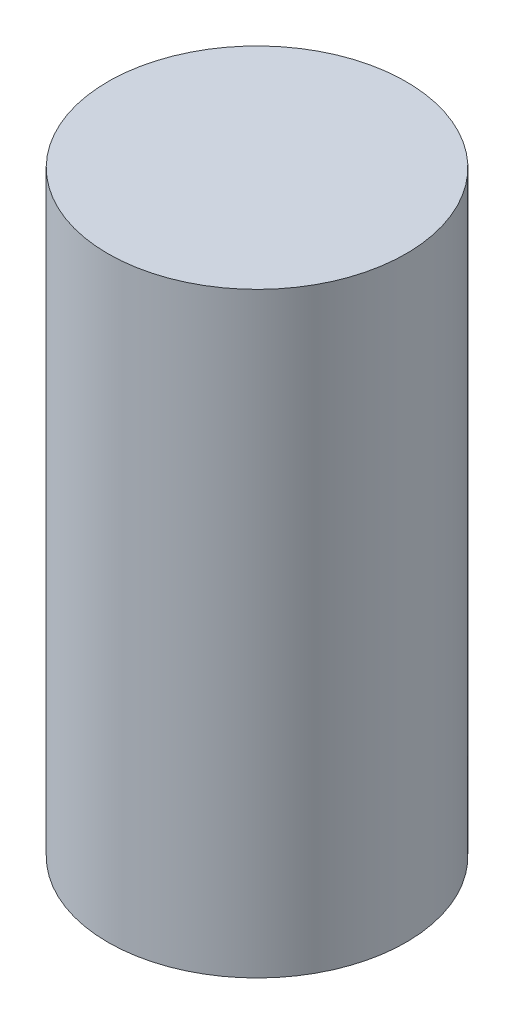
SolidWorks part; units mm, degrees
ref_plane "Front Plane" through (0, 0, 0) normal (0, 0, 1) x (1, 0, 0)
ref_plane "Top Plane" through (0, 0, 0) normal (0, 1, 0) x (1, 0, 0)
ref_plane "Right Plane" through (0, 0, 0) normal (1, 0, 0) x (0, 0, -1)
sketch "Sketch1" plane through (0, 0, 0) normal (0, 1, 0) x (1, 0, 0)
  circle A0 centre (0, 0) radius 1
  dimension "D1" = 2
extrude "Boss-Extrude1" add sketch "Sketch1" along normal blind 4
